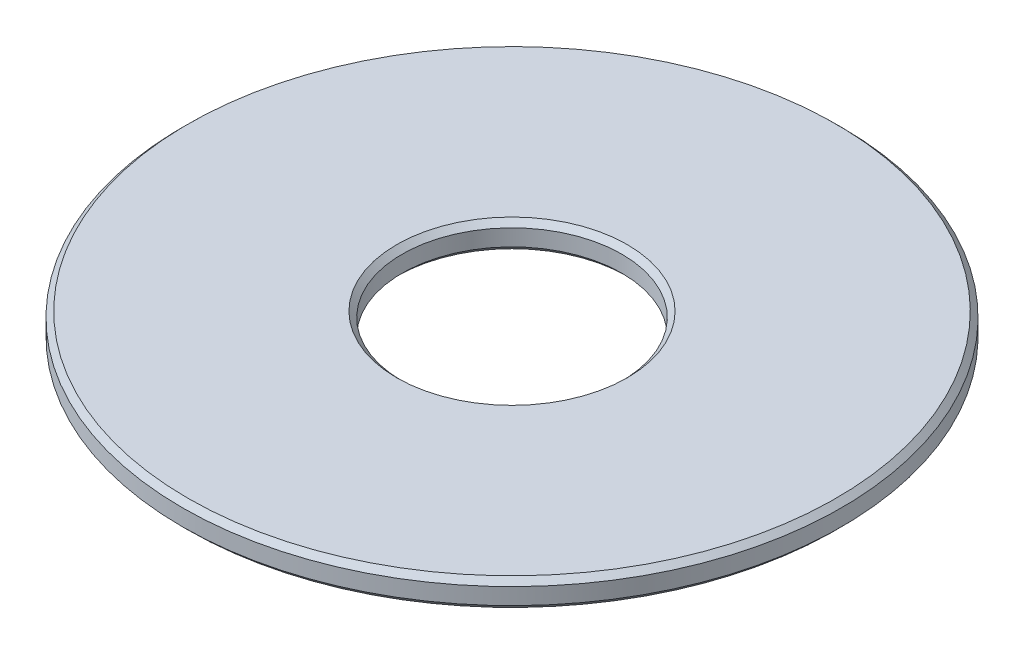
SolidWorks part; units mm, degrees
material "1023 Carbon Steel Sheet (SS)"
ref_plane "Front Plane" through (0, 0, 0) normal (0, 0, 1) x (1, 0, 0)
ref_plane "Top Plane" through (0, 0, 0) normal (0, 1, 0) x (1, 0, 0)
ref_plane "Right Plane" through (0, 0, 0) normal (1, 0, 0) x (0, 0, -1)
sketch "Sketch1" plane through (0, 0, 0) normal (0, 1, 0) x (1, 0, 0)
  circle A0 centre (0, 0) radius 2
  circle A1 centre (0, 0) radius 6
  dimension "D1" = 4
  dimension "D2" = 12
extrude "Boss-Extrude1" add sketch "Sketch1" along normal blind 0.5
chamfer "Chamfer1" distance 0.1 angle 45 4 edges at (0, 0, 2) (0, 0, 6) (0, 0.5, 2) (0, 0.5, 6)
